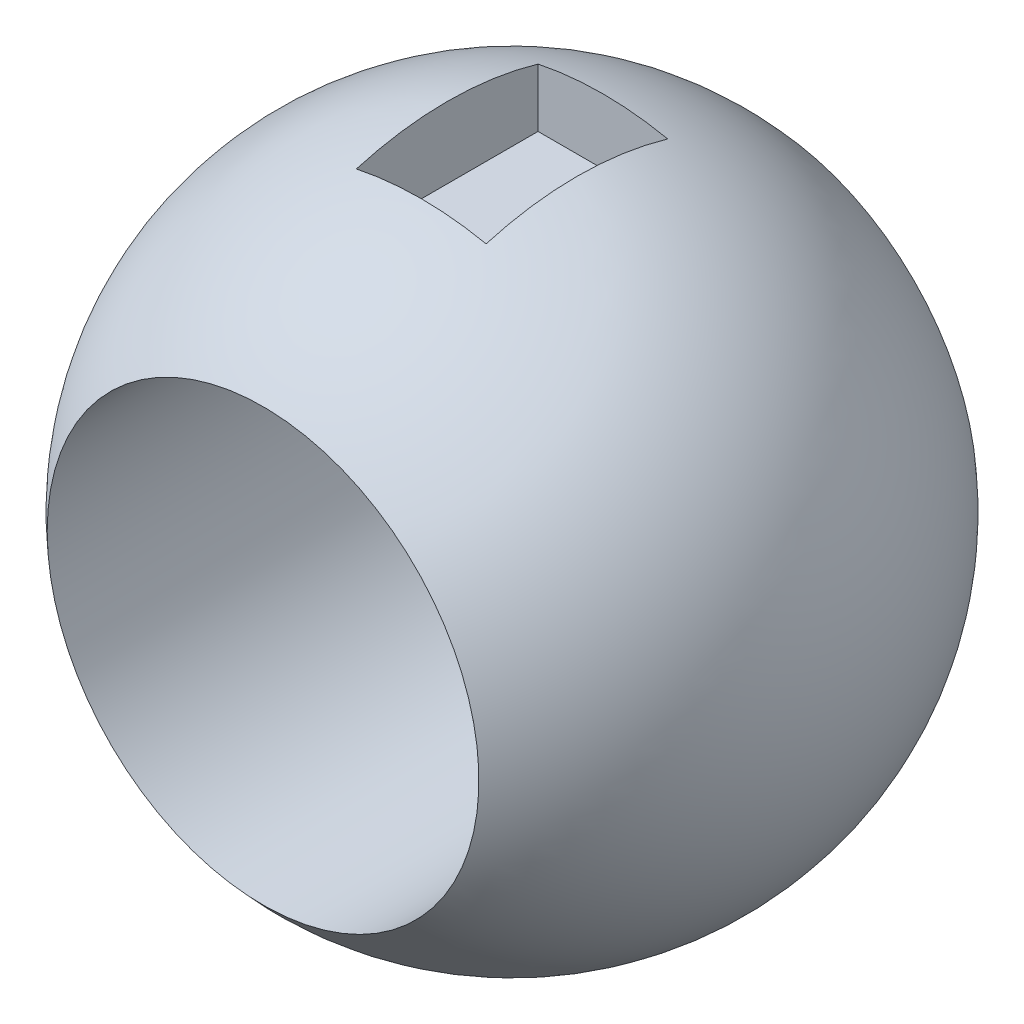
SolidWorks part; units mm, degrees
ref_plane "Front Plane" through (0, 0, 0) normal (0, 0, 1) x (1, 0, 0)
ref_plane "Top Plane" through (0, 0, 0) normal (0, 1, 0) x (1, 0, 0)
ref_plane "Right Plane" through (0, 0, 0) normal (1, 0, 0) x (0, 0, -1)
sketch "Sketch4" plane through (0, 0, 0) normal (0, 1, 0) x (1, 0, 0)
  line L0 (0, 17.4871) -> (0, -17.4871) construction
  line L1 (-12, 22.3866) -> (0, 22.3866)
  line L2 (0, 22.3866) -> (0, -22.3866)
  line L3 (0, -22.3866) -> (-12, -22.3866)
  arc A0 (-12, -22.3866) -> (-12, 22.3866) centre (0, 0) cw
  point P6 (0, 0)
  dimension "D1" = 25.4
  dimension "D2" = 12
revolve "Revolve4" add sketch "Sketch4" angle 360 about L0
sketch "Sketch5" plane through (0, 0, 22.3866) normal (0, 0, 1) x (1, 0, 0)
  circle A0 centre (0, 0) radius 16.637
  dimension "D1" = 33.274
extrude "Cut-Extrude2" cut sketch "Sketch5" against normal through all
ref_plane "Plane1" through (0, 25.4, 0) normal (0, 1, 0) x (1, 0, 0)
sketch "Sketch6" plane through (0, 25.4, 0) normal (0, 1, 0) x (1, 0, 0)
  line L1 (5, -7) -> (-5, -7)
  line L2 (5, -7) -> (5, 7)
  line L3 (5, 7) -> (-5, 7)
  line L4 (-5, -7) -> (-5, 7)
  line L5 (5, -7) -> (-5, 7) construction
  line L6 (5, 7) -> (-5, -7) construction
  point P0 (0, 0)
  dimension "D1" = 10
  dimension "D2" = 14
extrude "Cut-Extrude3" cut sketch "Sketch6" against normal blind 6
